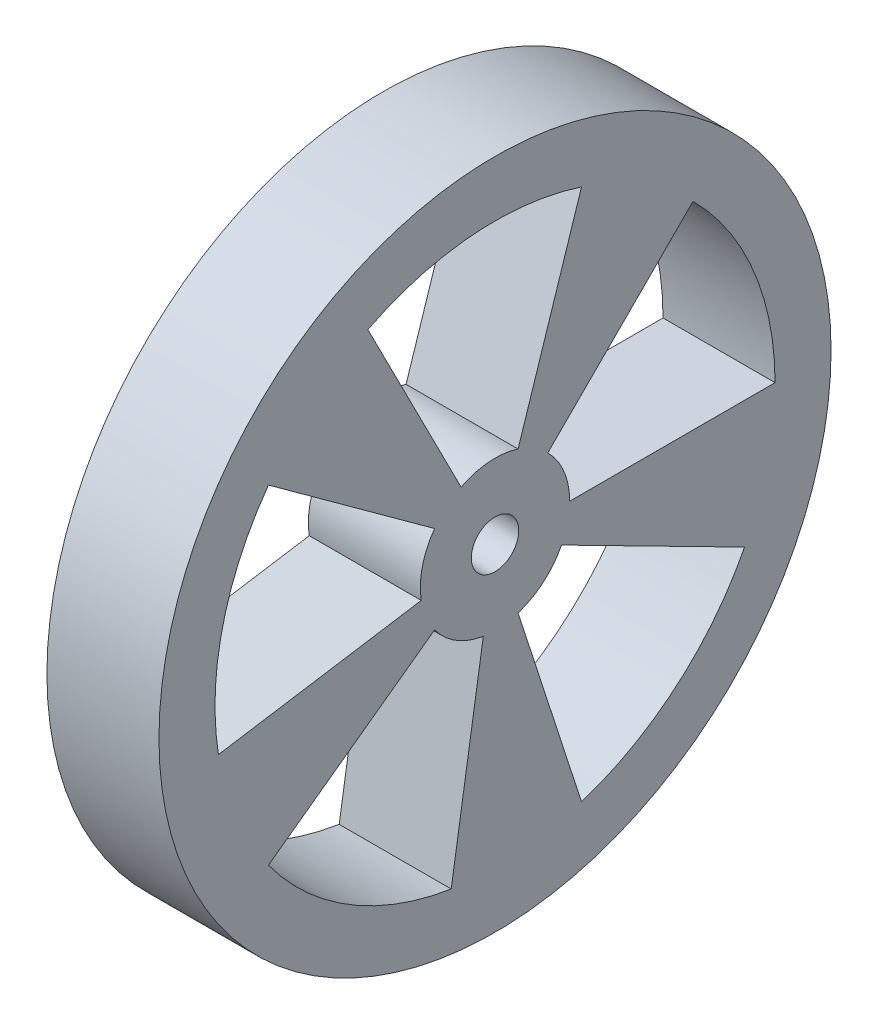
SolidWorks part; units mm, degrees
ref_plane "Front Plane" through (0, 0, 0) normal (0, 0, 1) x (1, 0, 0)
ref_plane "Top Plane" through (0, 0, 0) normal (0, 1, 0) x (1, 0, 0)
ref_plane "Right Plane" through (0, 0, 0) normal (1, 0, 0) x (0, 0, -1)
sketch "Sketch1" plane through (0, 0, 0) normal (1, 0, 0) x (0, 0, -1)
  circle A0 centre (0, 0) radius 90
  dimension "D1" = 180
extrude "Boss-Extrude1" add sketch "Sketch1" along normal blind 30
sketch "Sketch2" plane through (0, 0, 0) normal (-1, 0, 0) x (0, 0, 1)
  circle A0 centre (0, 0) radius 6.35
  dimension "D1" = 12.7
extrude "Cut-Extrude2" cut sketch "Sketch2" against normal through all
sketch "Sketch3" plane through (0, 0, 0) normal (-1, 0, 0) x (0, 0, 1)
  line L0 (-20, 0) -> (-75, 0)
  line L1 (-53.033, 53.033) -> (-14.1421, 14.1421)
  arc A0 (-75, 0) -> (-53.033, 53.033) centre (0, 0) cw
  arc A1 (-14.1421, 14.1421) -> (-20, 0) centre (0, 0) ccw
  dimension "D1" = 20
  dimension "D2" = 75
  dimension "D3" = 45
extrude "Cut-Extrude3" cut sketch "Sketch3" against normal blind 30
pattern_circular "CirPattern1" count 5 over 360 about axis through (0, 0, 0) along (1, 0, 0) of "Cut-Extrude3"
